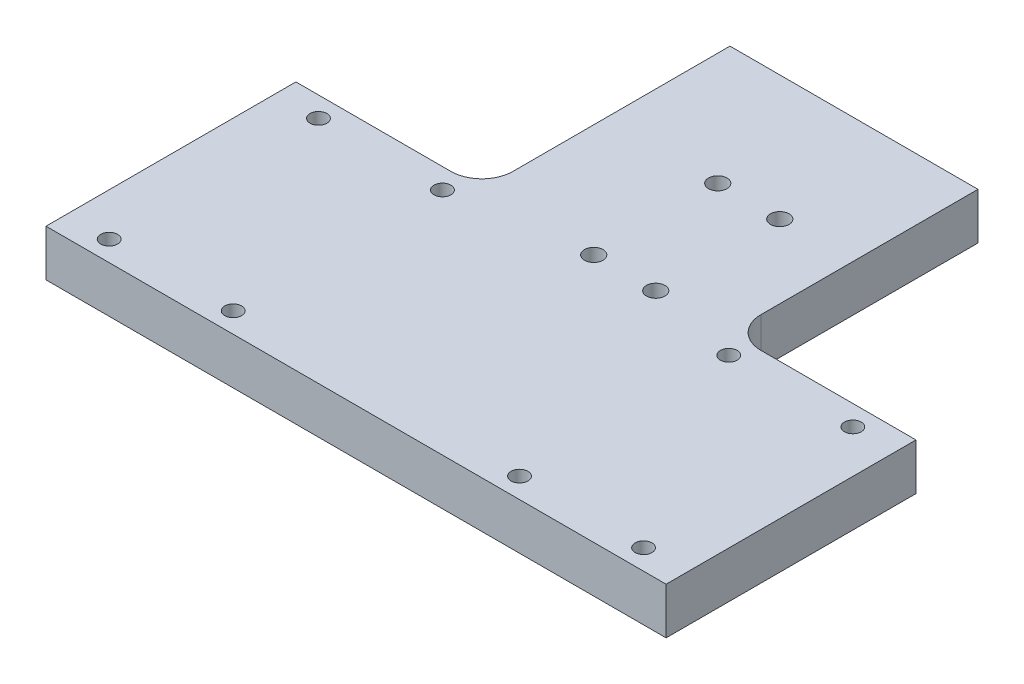
SolidWorks part; units mm, degrees
ref_plane "Front Plane" through (0, 0, 0) normal (0, 0, 1) x (1, 0, 0)
ref_plane "Top Plane" through (0, 0, 0) normal (0, 1, 0) x (1, 0, 0)
ref_plane "Right Plane" through (0, 0, 0) normal (1, 0, 0) x (0, 0, -1)
sketch "Sketch1" plane through (0, 0, 0) normal (0, 1, 0) x (1, 0, 0)
  line L0 (32.7703, 9.7661) -> (70.8703, 9.7661)
  line L1 (-18.0297, 60.5661) -> (32.7703, 60.5661)
  line L2 (-18.0297, 60.5661) -> (-18.0297, 9.7661)
  line L3 (70.8703, -41.4149) -> (-56.1297, -41.4149)
  line L4 (32.7703, 60.5661) -> (32.7703, 9.7661)
  line L5 (-56.1297, 9.7661) -> (-18.0297, 9.7661)
  line L6 (-56.1297, 9.7661) -> (-56.1297, -41.4149)
  line L8 (70.8703, 9.7661) -> (70.8703, -41.4149)
  dimension "D1" = 50.8
  dimension "D2" = 50.8
  dimension "D3" = 51.181
  dimension "D4" = 127
extrude "Boss-Extrude1" add sketch "Sketch1" along normal blind 9.525
hole_wizard "#8-32 Tapped Hole1" positions "Sketch3" profile "Sketch2" tap size "#8-32" standard "ANSI Inch" end condition through all
sketch "Sketch3" plane through (0, 9.525, 0) normal (0, 1, 0) x (1, 0, 0)
  line L0 (7.3703, 60.5661) -> (7.3703, -41.4149) construction
  line L1 (32.7703, 60.5661) -> (-18.0297, 60.5661) construction
  line L2 (-56.1297, -41.4149) -> (70.8703, -41.4149) construction
  line L5 (-34.654, 9.7661) -> (-34.654, -41.4149) construction
  line L9 (-56.1297, -15.8244) -> (70.8703, -15.8244) construction
  line L10 (-56.1297, 9.7661) -> (-56.1297, -41.4149) construction
  line L11 (70.8703, -41.4149) -> (70.8703, 9.7661) construction
  point P0 (-47.354, 5.6069)
  point P39 (-47.354, -37.2556)
  point P40 (-21.954, -37.2556)
  point P41 (-21.954, 5.6069)
  point P42 (62.0946, 5.6069)
  point P43 (62.0946, -37.2556)
  point P44 (36.6946, -37.2556)
  point P45 (36.6946, 5.6069)
  dimension "D1" = 25.4
  dimension "D2" = 42.8625
  dimension "D3" = 21.4757
sketch "Sketch2" plane through (-47.354, 9.525, -5.6069) normal (1, 0, 0) x (0, 0, 1)
  line L0 (0, 0) -> (0, 9.525)
  line L1 (0, 9.525) -> (1.7272, 9.525)
  line L2 (1.7272, 9.525) -> (1.7272, 0)
  line L5 (1.7272, 0) -> (0, 0)
  line L11 (0, -6.35) -> (0, 107.95) construction
  dimension "Thru Tap Drill Dia." = 3.4544
  dimension "Thru Tap Drill Depth" = 9.525
cosmetic thread "Hole Thread1" parameters "D2"=4.1656
cosmetic thread "Hole Thread2" parameters "D2"=4.1656
cosmetic thread "Hole Thread3" parameters "D2"=4.1656
cosmetic thread "Hole Thread4" parameters "D2"=4.1656
cosmetic thread "Hole Thread5" parameters "D2"=4.1656
cosmetic thread "Hole Thread6" parameters "D2"=4.1656
cosmetic thread "Hole Thread7" parameters "D2"=4.1656
cosmetic thread "Hole Thread8" parameters "D2"=4.1656
hole_wizard "#10-24 Tapped Hole1" positions "Sketch5" profile "Sketch4" tap size "#10-24" standard "ANSI Inch" end condition through all
sketch "Sketch5" plane through (0, 9.525, 0) normal (0, 1, 0) x (1, 0, 0)
  line L0 (-28.2194, 22.2756) -> (42.8512, 22.2756) construction
  line L3 (70.8703, -15.8244) -> (-56.1297, -15.8244) construction
  line L4 (70.8703, -41.4149) -> (70.8703, 9.7661) construction
  line L5 (-56.1297, 9.7661) -> (-56.1297, -41.4149) construction
  line L8 (27.9189, 64.3116) -> (27.9189, -52.9619) construction
  line L9 (-13.1783, -57.4166) -> (-13.1783, 67.037) construction
  point P0 (5.0589, 34.9756)
  point P2 (17.7589, 34.9756)
  point P32 (5.0589, 9.5756)
  point P33 (17.7589, 9.5756)
  dimension "D1" = 12.7
  dimension "D2" = 38.1
  dimension "D3" = 25.4
  dimension "D4" = 42.9514
  dimension "D5" = 10.16
  dimension "D6" = 42.9514
sketch "Sketch4" plane through (5.0589, 9.525, -34.9756) normal (1, 0, 0) x (0, 0, 1)
  line L0 (0, 0) -> (0, 9.525)
  line L1 (0, 9.525) -> (1.8986, 9.525)
  line L2 (1.8986, 9.525) -> (1.8986, 0)
  line L5 (1.8986, 0) -> (0, 0)
  line L11 (0, -6.35) -> (0, 107.95) construction
  dimension "Thru Tap Drill Dia." = 3.7973
  dimension "Thru Tap Drill Depth" = 9.525
cosmetic thread "Hole Thread9" parameters "D2"=4.826
cosmetic thread "Hole Thread10" parameters "D2"=4.826
cosmetic thread "Hole Thread11" parameters "D2"=4.826
cosmetic thread "Hole Thread12" parameters "D2"=4.826
hole_wizard "1/4-20 Tapped Hole1" positions "Sketch7" profile "Sketch6" tap size "1/4-20" standard "ANSI Inch"
sketch "Sketch7" plane through (0, 0, -60.5661) normal (0, 0, -1) x (-1, 0, 0)
  line L0 (-7.3703, 0) -> (-7.3703, 9.525) construction
  line L1 (-32.7703, 0) -> (18.0297, 0) construction
  line L2 (-32.7703, 9.525) -> (18.0297, 9.525) construction
  point P0 (8.5047, 4.7625)
  point P2 (-7.3703, 4.7625)
  point P4 (-23.2453, 4.7625)
  dimension "D1" = 15.875
  dimension "D2" = 15.875
sketch "Sketch6" plane through (-8.5047, 4.7625, -60.5661) normal (1, 0, 0) x (0, 1, 0)
  line L0 (0, 0) -> (0, 20.5838)
  line L1 (0, 20.5838) -> (2.5527, 19.05)
  line L2 (2.5527, 19.05) -> (2.5527, 0)
  line L5 (2.5527, 0) -> (0, 0)
  line L10 (0, 20.5838) -> (-2.5527, 19.05) construction
  line L11 (0, -6.35) -> (0, 107.95) construction
  dimension "Tap Drill Dia." = 5.1054
  dimension "Tap Drill Depth" = 19.05
  dimension "Drill Angle" = 118
cosmetic thread "Hole Thread13" parameters "D1"=19.05, "D2"=6.35
cosmetic thread "Hole Thread14" parameters "D1"=19.05, "D2"=6.35
cosmetic thread "Hole Thread15" parameters "D1"=19.05, "D2"=6.35
fillet "Fillet1" radius 6.35 2 edges at (-18.0297, 4.7625, -9.7661) (32.7703, 4.7625, -9.7661)
